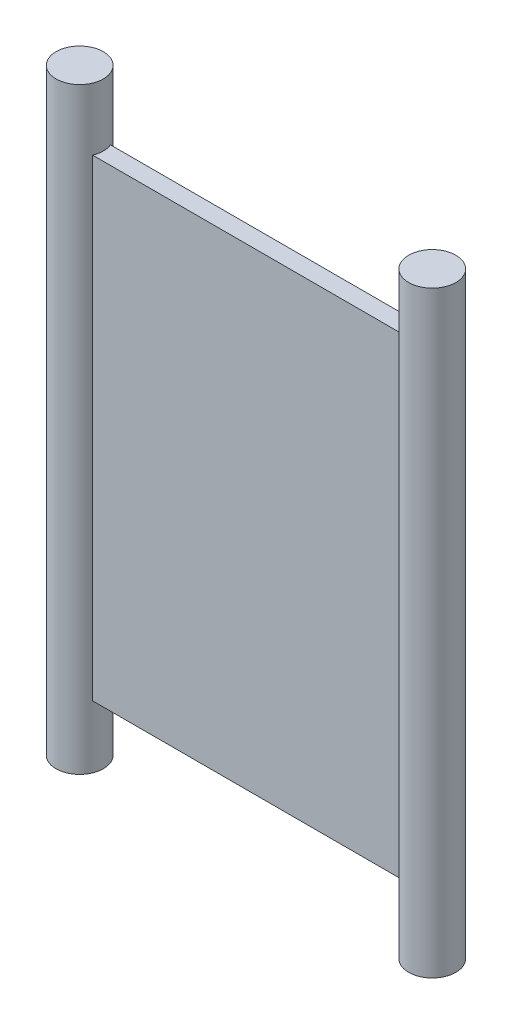
SolidWorks part; units mm, degrees
ref_plane "Front Plane" through (0, 0, 0) normal (0, 0, 1) x (1, 0, 0)
ref_plane "Top Plane" through (0, 0, 0) normal (0, 1, 0) x (1, 0, 0)
ref_plane "Right Plane" through (0, 0, 0) normal (1, 0, 0) x (0, 0, -1)
sketch "Sketch1" plane through (0, 0, 0) normal (0, 1, 0) x (1, 0, 0)
  line L1 (9.885, 0.5) -> (-9.885, 0.5)
  line L2 (9.885, 0.5) -> (9.885, -0.5)
  line L3 (9.885, -0.5) -> (-9.885, -0.5)
  line L4 (-9.885, 0.5) -> (-9.885, -0.5)
  line L5 (9.885, 0.5) -> (-9.885, -0.5) construction
  line L6 (9.885, -0.5) -> (-9.885, 0.5) construction
  point P0 (0, 0)
  dimension "D1" = 19.77
  dimension "D3" = 1
extrude "Boss-Extrude1" add sketch "Sketch1" along normal blind 26.5
ref_plane "Plane1" through (0, 13.25, 0) normal (0, 1, 0) x (1, 0, 0)
sketch "Sketch2" plane through (0, 13.25, 0) normal (0, 1, 0) x (1, 0, 0)
  line L0 (9.885, -0.5) -> (9.885, 0.5) construction
  line L1 (-9.885, 0.5) -> (-9.885, -0.5) construction
  line L2 (9.885, -0.5) -> (9.885, 0.5) construction
  line L3 (-9.885, 0.5) -> (-9.885, -0.5) construction
  circle A0 centre (-9.885, 0) radius 1.325
  circle A1 centre (9.885, 0) radius 1.325
  dimension "D1" = 2.65
extrude "Boss-Extrude2" add sketch "Sketch2" along normal mid plane 33.5
